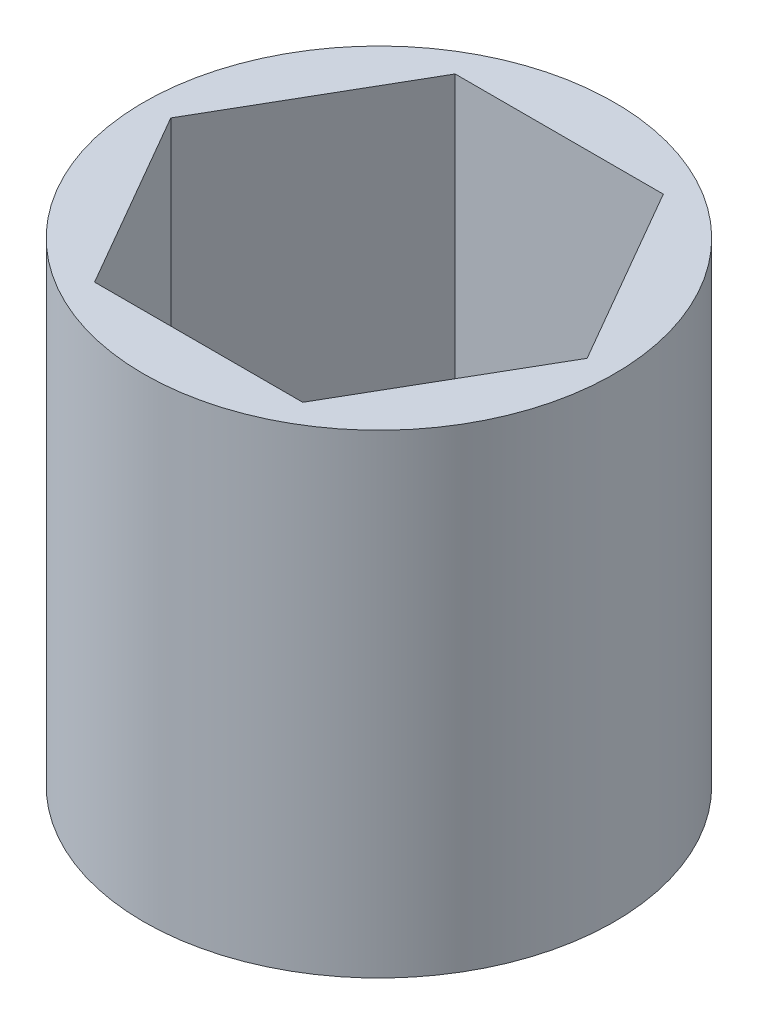
SolidWorks part; units mm, degrees
ref_plane "Front Plane" through (0, 0, 0) normal (0, 0, 1) x (1, 0, 0)
ref_plane "Top Plane" through (0, 0, 0) normal (0, 1, 0) x (1, 0, 0)
ref_plane "Right Plane" through (0, 0, 0) normal (1, 0, 0) x (0, 0, -1)
sketch "Sketch1" plane through (0, 0, 0) normal (0, 1, 0) x (1, 0, 0)
  line L1 (5.5726, 0) -> (2.7863, 4.826)
  line L2 (2.7863, 4.826) -> (-2.7863, 4.826)
  line L3 (-2.7863, 4.826) -> (-5.5726, 0)
  line L4 (-5.5726, 0) -> (-2.7863, -4.826)
  line L5 (-2.7863, -4.826) -> (2.7863, -4.826)
  line L6 (2.7863, -4.826) -> (5.5726, 0)
  circle A0 centre (0, 0) radius 6.2992
  circle A1 centre (0, 0) radius 4.826 construction
  dimension "D1" = 12.5984
  dimension "D2" = 9.652
extrude "Boss-Extrude1" add sketch "Sketch1" along normal blind 12.7
